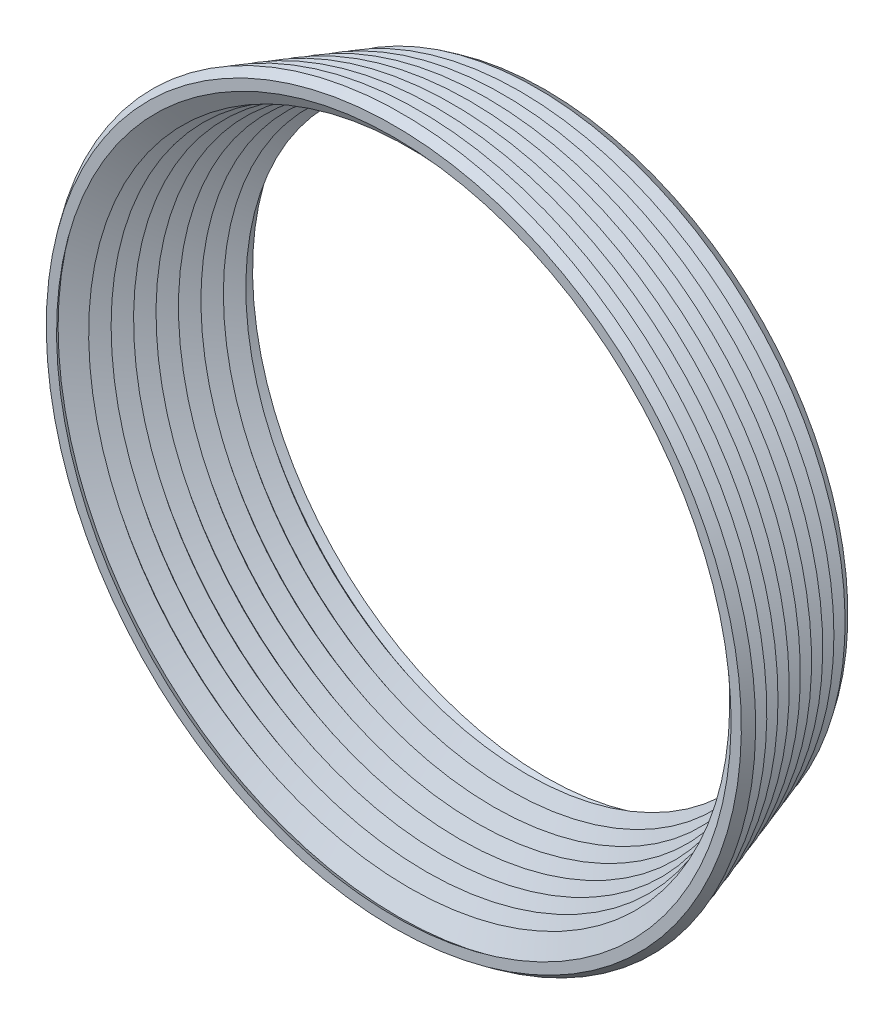
SolidWorks part; units mm, degrees
ref_plane "Front Plane" through (0, 0, 0) normal (0, 0, 1) x (1, 0, 0)
ref_plane "Top Plane" through (0, 0, 0) normal (0, 1, 0) x (1, 0, 0)
ref_plane "Right Plane" through (0, 0, 0) normal (1, 0, 0) x (0, 0, -1)
sketch "Sketch1" plane through (0, 0, 0) normal (1, 0, 0) x (0, 0, -1)
  line L0 (-9, 0) -> (9, 0) construction
  line L1 (9, 36) -> (8, 36.67)
  line L2 (8, 36.67) -> (7, 35.33)
  line L3 (7, 35.33) -> (6, 37.34)
  line L4 (6, 37.34) -> (5, 36)
  line L5 (5, 36) -> (4, 38.01)
  line L6 (4, 38.01) -> (3, 36.67)
  line L7 (3, 36.67) -> (2, 38.68)
  line L8 (2, 38.68) -> (1, 37.34)
  line L9 (1, 37.34) -> (0, 39.35)
  line L10 (0, 39.35) -> (-1, 38.01)
  line L11 (-1, 38.01) -> (-2, 40.02)
  line L12 (-2, 40.02) -> (-3, 38.68)
  line L13 (-3, 38.68) -> (-4, 40.69)
  line L14 (-4, 40.69) -> (-5, 39.35)
  line L15 (-5, 39.35) -> (-6, 41.36)
  line L16 (-6, 41.36) -> (-7, 40.02)
  line L17 (-7, 40.02) -> (-8, 42.03)
  line L18 (-8, 42.03) -> (-9, 41.33)
  line L19 (9, 36) -> (9, 0) construction
  line L20 (9, 36) -> (9, 0)
  line L21 (-9, 41.33) -> (-9, 0)
  line L22 (-9, 0) -> (9, 0)
  point P42 (0, 0)
  dimension "D1" = 18
  dimension "D2" = 36
  dimension "D3" = 2
  dimension "D4" = 2
  dimension "D5" = 2
  dimension "D6" = 2
  dimension "D7" = 2
  dimension "D8" = 2
  dimension "D9" = 2
  dimension "D10" = 2
  dimension "D11" = 2
  dimension "D12" = 1
  dimension "D13" = 1
  dimension "D14" = 1
  dimension "D15" = 1
  dimension "D16" = 1
  dimension "D17" = 1
  dimension "D18" = 1
  dimension "D19" = 1
  dimension "D20" = 1
  dimension "D21" = 41.33
  dimension "D22" = 0.67
  dimension "D23" = 1.34
  dimension "D24" = 0.67
  dimension "D25" = 1.34
  dimension "D26" = 0.67
  dimension "D27" = 1.34
  dimension "D28" = 0.67
  dimension "D29" = 1.34
  dimension "D30" = 0.67
  dimension "D31" = 1.34
  dimension "D32" = 0.67
  dimension "D33" = 1.34
  dimension "D34" = 0.67
  dimension "D35" = 1.34
  dimension "D36" = 0.67
  dimension "D37" = 1.34
  dimension "D38" = 0.67
revolve "Revolve1" add sketch "Sketch1" angle 360 about L22
shell "Shell1" thickness 1
